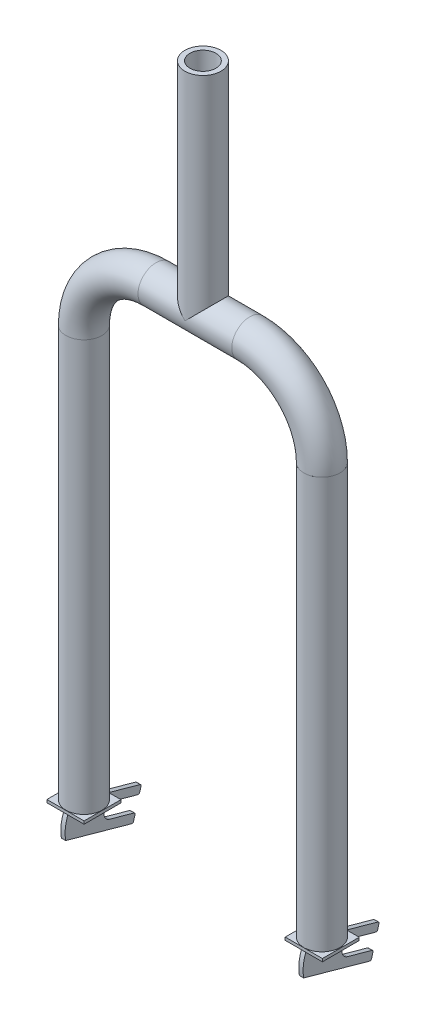
SolidWorks part; units mm, degrees
ref_plane "Front Plane" through (0, 0, 0) normal (0, 0, 1) x (1, 0, 0)
ref_plane "Top Plane" through (0, 0, 0) normal (0, 1, 0) x (1, 0, 0)
ref_plane "Right Plane" through (0, 0, 0) normal (1, 0, 0) x (0, 0, -1)
sketch "Sketch1" plane through (0, 0, 0) normal (0, 0, 1) x (1, 0, 0)
  line L0 (0, 0) -> (0, 150)
  line L1 (0, 0) -> (0, -370) construction
  line L2 (32.5, 0) -> (-32.5, 0)
  line L3 (-82.5, -50) -> (-82.5, -335)
  line L4 (0, -297) -> (0, 297) construction
  line L5 (82.5, -50) -> (82.5, -335)
  arc A0 (-82.5, -50) -> (-32.5, 0) centre (-32.5, -50) cw
  arc A1 (82.5, -50) -> (32.5, 0) centre (32.5, -50) ccw
  dimension "D1" = 50
other "New folder FORK ROD(1)"
ref_plane "Plane1" through (-82.5, -50, 0) normal (0, -1, 0) x (1, 0, 0)
sketch "Sketch11" plane through (-82.5, -50, 0) normal (0, -1, 0) x (1, 0, 0)
  circle A0 centre (0, 0) radius 12.52
  circle A1 centre (0, 0) radius 9.02
  point P4 (0, 0)
other "New folder FORK ROD(2)"
ref_plane "Plane2" through (0, 0, 0) normal (0, 1, 0) x (-1, 0, 0)
sketch "Sketch12" plane through (0, 0, 0) normal (0, 1, 0) x (-1, 0, 0)
  circle A0 centre (0, 0) radius 12.52
  circle A1 centre (0, 0) radius 9.02
  point P4 (0, 0)
ref_plane "Plane3" through (0, -335, 0) normal (0, -1, 0) x (-1, 0, 0)
sketch "Sketch13" plane through (0, -335, 0) normal (0, -1, 0) x (-1, 0, 0)
  line L1 (95.5014, -12.6707) -> (69.7412, -12.6707)
  line L2 (95.5014, -12.6707) -> (95.5014, 12.8801)
  line L3 (95.5014, 12.8801) -> (69.7412, 12.8801)
  line L4 (69.7412, -12.6707) -> (69.7412, 12.8801)
extrude "Boss-Extrude1" add sketch "Sketch13" along normal blind 2 separate body
mirror "Mirror1" about plane through (0, 0, 0) normal (1, 0, 0) of bodies 107
ref_plane "Plane4" through (82.5, 0, 0) normal (1, 0, 0) x (0, 0, -1)
sketch "Sketch14" plane through (82.5, 0, 0) normal (1, 0, 0) x (0, 0, -1)
  line L0 (12.8801, -337) -> (12.8801, -347.0093) construction
  line L1 (38.1055, -345.0701) -> (37.1537, -348.4843)
  line L2 (35.9219, -349.179) -> (18.816, -344.4105)
  line L3 (18.816, -344.4105) -> (16.1307, -354.0432) construction
  line L5 (12.8801, -337) -> (37.4107, -343.8383)
  line L6 (16.1307, -354.0432) -> (33.2367, -358.8117)
  line L7 (33.9314, -360.0435) -> (32.887, -363.7902)
  line L8 (31.6552, -364.485) -> (-14.1548, -351.7148)
  line L14 (-12.6707, -337) -> (12.8801, -337)
  arc A0 (-12.6707, -337) -> (-14.1548, -351.7148) centre (12.8801, -347.0093) ccw
  arc A2 (18.816, -344.4105) -> (16.1307, -354.0432) centre (17.4733, -349.2268) ccw
  arc A3 (38.1055, -345.0701) -> (37.4107, -343.8383) centre (37.1422, -344.8016) ccw
  arc A4 (35.9219, -349.179) -> (37.1537, -348.4843) centre (36.1905, -348.2157) ccw
  arc A5 (32.887, -363.7902) -> (31.6552, -364.485) centre (31.9237, -363.5217) cw
  arc A6 (33.9314, -360.0435) -> (33.2367, -358.8117) centre (32.9681, -359.775) ccw
  dimension "D1" = 1
  dimension "D2" = 1
  dimension "D3" = 1
extrude "Boss-Extrude2" add sketch "Sketch14" along normal mid plane 3 separate body
mirror "Mirror2" about plane through (0, 0, 0) normal (1, 0, 0) of bodies 112
other "Trim/Extend1"
